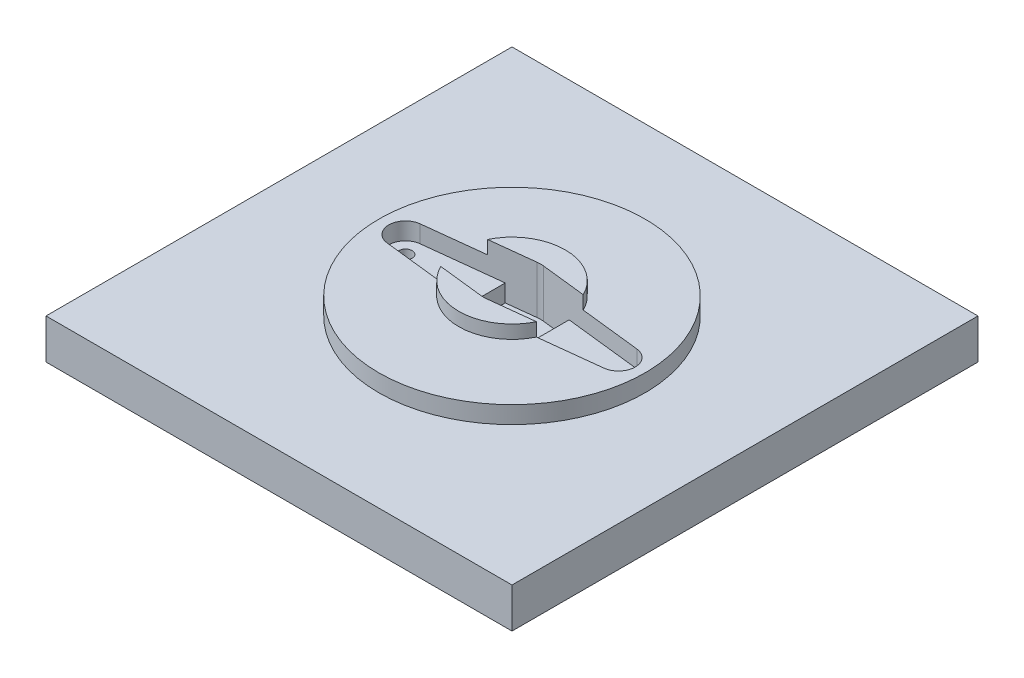
SolidWorks part; units mm, degrees
ref_plane "Front Plane" through (0, 0, 0) normal (0, 0, 1) x (1, 0, 0)
ref_plane "Top Plane" through (0, 0, 0) normal (0, 1, 0) x (1, 0, 0)
ref_plane "Right Plane" through (0, 0, 0) normal (1, 0, 0) x (0, 0, -1)
sketch "Sketch1" plane through (0, 0, 0) normal (0, 1, 0) x (1, 0, 0)
  line L1 (-35, 35) -> (35, 35)
  line L2 (-35, 35) -> (-35, -35)
  line L3 (-35, -35) -> (35, -35)
  line L4 (35, 35) -> (35, -35)
  line L5 (-35, 35) -> (35, -35) construction
  line L6 (-35, -35) -> (35, 35) construction
  point P0 (0, 0)
  dimension "D1" = 70
  dimension "D2" = 70
extrude "Boss-Extrude1" add sketch "Sketch1" along normal blind 6
sketch "Sketch2" plane through (0, 6, 0) normal (0, 1, 0) x (1, 0, 0)
  line L1 (-16.2812, -2.4841) -> (-0.4838, -4.2727)
  line L2 (-16.2812, 2.4841) -> (-0.4838, 4.2727)
  line L3 (0.4838, -4.2727) -> (16.2812, -2.4841)
  line L4 (0.4838, 4.2727) -> (16.2812, 2.4841)
  circle A0 centre (0, 0) radius 20
  arc A1 (-0.4838, -4.2727) -> (0.4838, -4.2727) centre (0, 0) ccw
  arc A2 (-16.2812, 2.4841) -> (-16.2812, -2.4841) centre (-16, 0) ccw
  arc A3 (16.2812, -2.4841) -> (16.2812, 2.4841) centre (16, 0) ccw
  arc A4 (0.4838, 4.2727) -> (-0.4838, 4.2727) centre (0, 0) ccw
  dimension "D1" = 40
  dimension "D2" = 8.6
  dimension "D3" = 5
  dimension "D4" = 5
  dimension "D5" = 32
  dimension "D6" = 16
extrude "Boss-Extrude6" add sketch "Sketch2" along normal blind 2.6
sketch "Sketch3" plane through (0, 6, 0) normal (0, 1, 0) x (1, 0, 0)
  line L0 (-16, 0) -> (16, 0) construction
  line L1 (0.4838, -4.2727) -> (16.2812, -2.4841) construction
  line L3 (-4.8, 3.784) -> (-4.8, -3.784)
  line L5 (4.8, 3.784) -> (4.8, -3.784)
  line L6 (-4.8, 3.784) -> (4.8, -3.784) construction
  line L7 (-4.8, -3.784) -> (4.8, 3.784) construction
  line L8 (0.4838, -4.2727) -> (16.2812, -2.4841) construction
  line L9 (-16.2812, -2.4841) -> (-0.4838, -4.2727) construction
  line L10 (16.2812, 2.4841) -> (0.4837, 4.2727) construction
  line L11 (-0.4838, 4.2727) -> (-16.2812, 2.4841) construction
  line L12 (0.4838, -4.2727) -> (4.8, -3.784)
  line L13 (-4.8, -3.784) -> (-0.4838, -4.2727)
  line L14 (4.8, 3.784) -> (0.4837, 4.2727)
  line L15 (-0.4838, 4.2727) -> (-4.8, 3.784)
  circle A0 centre (-16, 0) radius 1 construction
  circle A2 centre (16, 0) radius 1 construction
  arc A3 (-0.4838, -4.2727) -> (0.4838, -4.2727) centre (0, 0) ccw construction
  arc A4 (0.4837, 4.2727) -> (-0.4838, 4.2727) centre (0, 0) ccw construction
  arc A5 (-0.4838, -4.2727) -> (0.4838, -4.2727) centre (0, 0) ccw
  arc A6 (0.4837, 4.2727) -> (-0.4838, 4.2727) centre (0, 0) ccw
  point P4 (0, 0)
  point P6 (0, 0)
  dimension "D2" = 2
  dimension "D3" = 2
  dimension "D4" = 9.6
  dimension "D1" = 32
extrude "Cut-Extrude1" cut sketch "Sketch3" against normal blind 2.6
sketch "Sketch4" plane through (0, 0, 0) normal (0, -1, 0) x (1, 0, 0)
  line L0 (0, 0) -> (0, -5.6053) construction
  circle A2 centre (16, 0) radius 3.5
  circle A7 centre (-16, 0) radius 3.5
  point P5 (0, 0)
  dimension "D2" = 7
  dimension "D1" = 32
extrude "Cut-Extrude2" cut sketch "Sketch4" against normal blind 1.6
sketch "Sketch5" plane through (0, 6, 0) normal (0, 1, 0) x (1, 0, 0)
  line L0 (0, 0) -> (16.3554, 0) construction
  line L1 (0, 0) -> (0, 3.0689) construction
  circle A0 centre (16, 0) radius 1
  circle A1 centre (-16, 0) radius 1
  dimension "D1" = 2
  dimension "D2" = 32
extrude "Cut-Extrude3" cut sketch "Sketch5" against normal up to surface (4.4 mm away) up to face at (-16, 1.6, -3.5)
sketch "Sketch6" plane through (0, 8.6, 0) normal (0, 1, 0) x (1, 0, 0)
  line L4 (16.2812, 2.4841) -> (0.4837, 4.2727) construction
  line L5 (-0.4838, 4.2727) -> (-16.2812, 2.4841) construction
  line L9 (0.4838, -4.2727) -> (16.2812, -2.4841) construction
  line L10 (7.187, 3.5138) -> (0.4837, 4.2727)
  line L11 (-0.4838, 4.2727) -> (-7.187, 3.5138)
  line L14 (0.4838, -4.2727) -> (7.187, -3.5138)
  line L15 (-16.2812, -2.4841) -> (-0.4838, -4.2727) construction
  line L16 (-7.187, -3.5138) -> (-0.4838, -4.2727)
  arc A0 (-7.187, -3.5138) -> (7.187, -3.5138) centre (0, 0) ccw
  arc A2 (0.4837, 4.2727) -> (-0.4838, 4.2727) centre (0, 0) ccw construction
  arc A3 (-0.4838, -4.2727) -> (0.4838, -4.2727) centre (0, 0) ccw construction
  arc A4 (0.4837, 4.2727) -> (-0.4838, 4.2727) centre (0, 0) ccw
  arc A5 (7.187, 3.5138) -> (-7.187, 3.5138) centre (0, 0) ccw
  arc A6 (-0.4838, -4.2727) -> (0.4838, -4.2727) centre (0, 0) ccw
  dimension "D1" = 8
extrude "Boss-Extrude7" add sketch "Sketch6" along normal blind 2
